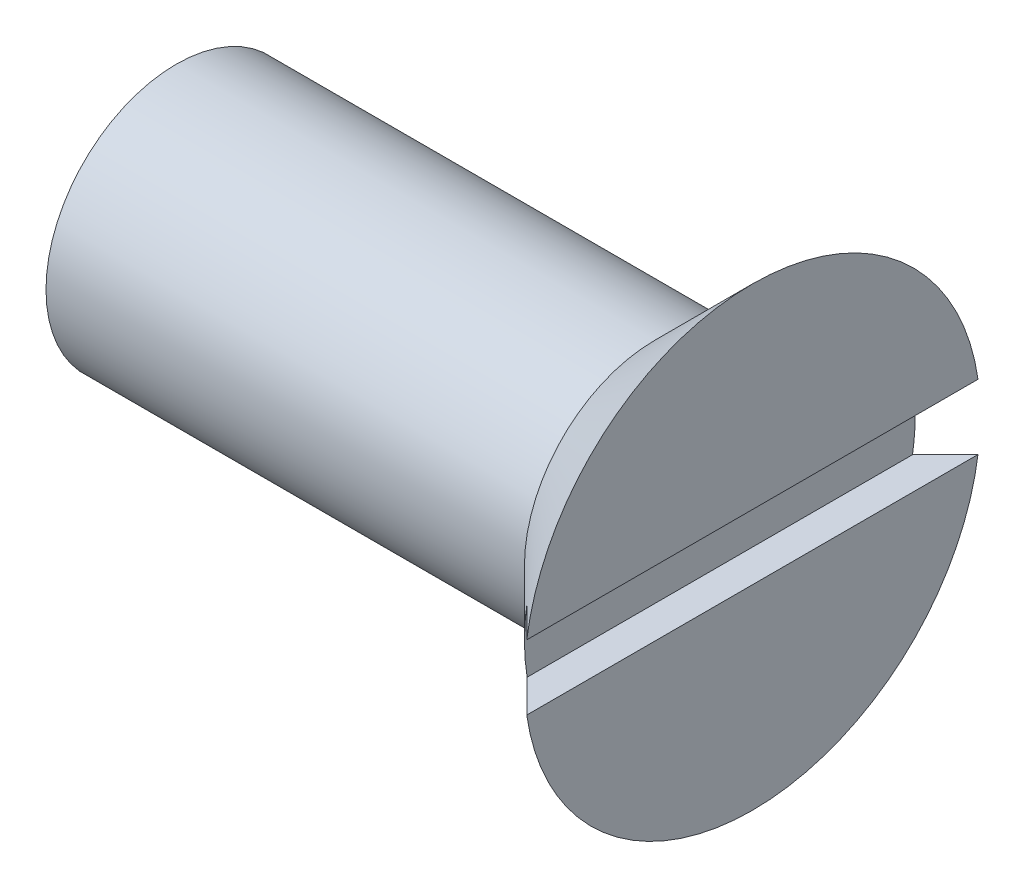
SolidWorks part; units mm, degrees
ref_plane "Front Plane" through (0, 0, 0) normal (0, 0, 1) x (1, 0, 0)
ref_plane "Top Plane" through (0, 0, 0) normal (0, 1, 0) x (1, 0, 0)
ref_plane "Right Plane" through (0, 0, 0) normal (1, 0, 0) x (0, 0, -1)
sketch "Sketch1" plane through (0, 0, 0) normal (0, 1, 0) x (1, 0, 0)
  line L0 (0, 0) -> (0, 11662.0861) construction
  line L1 (0, 0) -> (11662.0861, 0) construction
  line L2 (-20, 0) -> (-17.6906, -4)
  line L3 (-17.6906, -4) -> (-3, -4)
  line L4 (-3, -4) -> (0, -7)
  line L5 (0, -7) -> (0, 0)
  line L6 (0, 0) -> (-20, 0)
  dimension "D1" = 20
  dimension "D2" = 45
  dimension "D3" = 3
  dimension "D4" = 8
  dimension "D5" = 60
revolve "Revolve1" add sketch "Sketch1" angle 360 about L6
sketch "Sketch2" plane through (0, 0, 0) normal (1, 0, 0) x (0, 0, -1)
  line L1 (-8.119, 1) -> (8.119, 1)
  line L2 (-8.119, 1) -> (-8.119, -1)
  line L3 (-8.119, -1) -> (8.119, -1)
  line L4 (8.119, 1) -> (8.119, -1)
  line L5 (-8.119, 1) -> (8.119, -1) construction
  line L6 (-8.119, -1) -> (8.119, 1) construction
  point P1 (0, 0)
  dimension "D1" = 2
extrude "Cut-Extrude1" cut sketch "Sketch2" against normal blind 1
